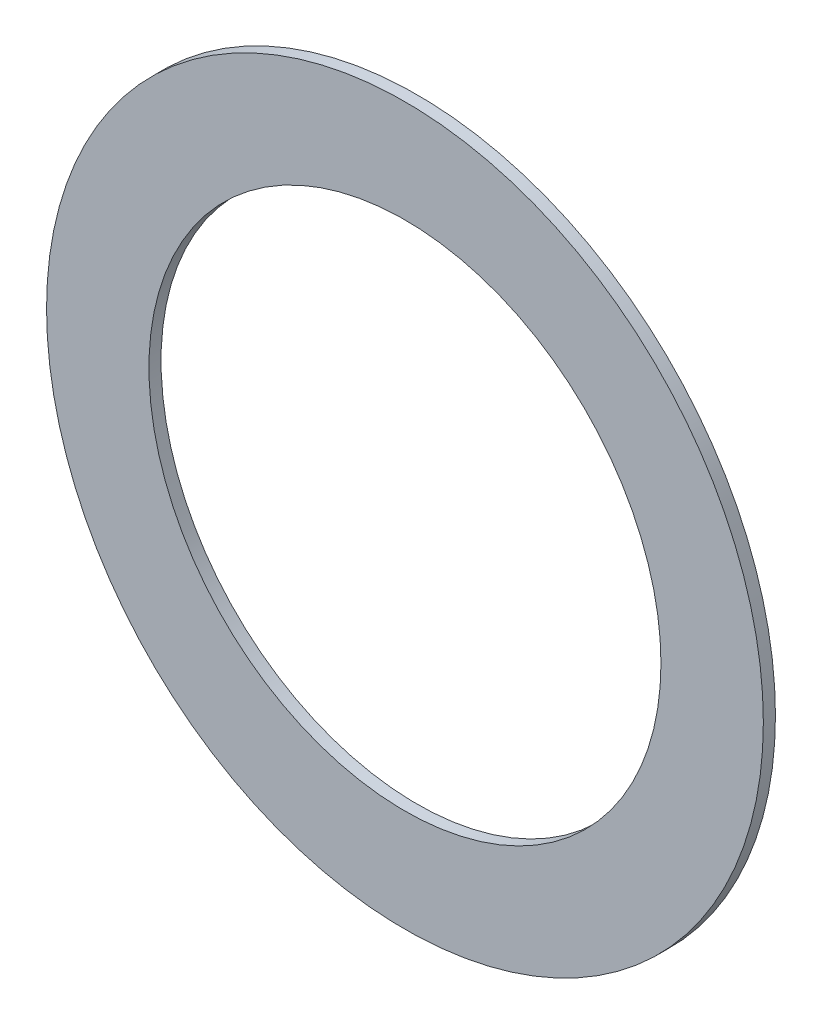
SolidWorks part; units mm, degrees
ref_plane "Front Plane" through (0, 0, 0) normal (1, 0, 0) x (0, 1, 0)
ref_plane "Top Plane" through (0, 0, 0) normal (0, 0, 1) x (0, 1, 0)
ref_plane "Right Plane" through (0, 0, 0) normal (0, 1, 0) x (-1, 0, 0)
sketch "Sketch1" plane through (0, 0, 0) normal (0, 0, 1) x (0, 1, 0)
  circle A0 centre (0, 0) radius 88.9
  circle A1 centre (0, 0) radius 63.5
  dimension "D1" = 177.8
  dimension "D2" = 25.4
extrude "Boss-Extrude1" add sketch "Sketch1" along normal blind 3
